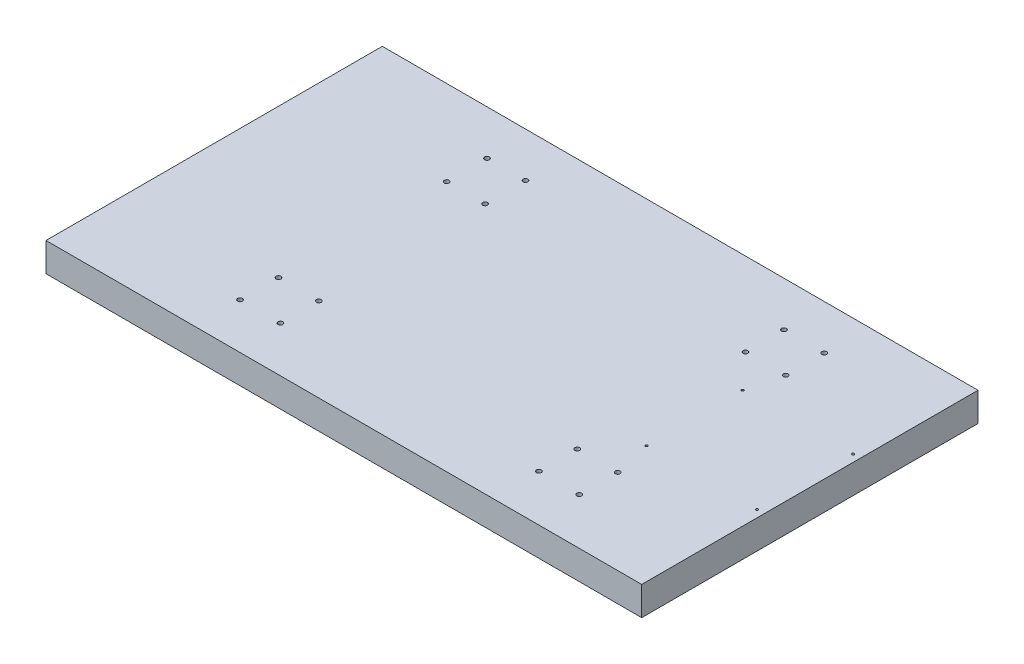
SolidWorks part; units mm, degrees
material "Plain Carbon Steel"
ref_plane "Front Plane" through (0, 0, 0) normal (0, 0, 1) x (1, 0, 0)
ref_plane "Top Plane" through (0, 0, 0) normal (0, 1, 0) x (1, 0, 0)
ref_plane "Right Plane" through (0, 0, 0) normal (1, 0, 0) x (0, 0, -1)
sketch "Sketch1" plane through (0, 0, 0) normal (0, 1, 0) x (1, 0, 0)
  line L0 (-418.465, 316.23) -> (418.465, 316.23) construction
  line L1 (418.465, 316.23) -> (418.465, -316.23) construction
  line L2 (418.465, -316.23) -> (-418.465, -316.23) construction
  line L3 (-418.465, -316.23) -> (-418.465, 316.23) construction
  line L4 (0, 316.23) -> (0, -316.23) construction
  line L6 (-876.3, 444.5) -> (876.3, 444.5)
  line L7 (-876.3, 444.5) -> (-876.3, -444.5)
  line L8 (-876.3, -444.5) -> (876.3, -444.5)
  line L9 (876.3, 444.5) -> (876.3, -444.5)
  line L10 (-876.3, 444.5) -> (876.3, -444.5) construction
  line L11 (-876.3, -444.5) -> (876.3, 444.5) construction
  point P10 (0, 0)
  point P11 (0, 0)
  dimension "D4" = 1752.6
  dimension "D5" = 889
extrude "Boss-Extrude1" add sketch "Sketch1" along normal blind 76.2
sketch "Sketch2" plane through (-876.3, 0, 0) normal (-1, 0, 0) x (0, 0, 1)
  line L4 (-444.5, 0) -> (444.5, 0)
  line L5 (444.5, 0) -> (444.5, 76.2)
  line L6 (444.5, 76.2) -> (-444.5, 76.2)
  line L7 (-444.5, 76.2) -> (-444.5, 0)
  line L8 (-444.5, 0) -> (444.5, 0)
  line L9 (444.5, 0) -> (444.5, 76.2)
  line L10 (444.5, 76.2) -> (-444.5, 76.2)
  line L11 (-444.5, 76.2) -> (-444.5, 0)
  dimension "D1" = 0
extrude "Boss-Extrude2" add sketch "Sketch2" along normal blind 330.2
sketch "Sketch4" plane through (876.3, 0, 0) normal (1, 0, 0) x (0, 0, -1)
  line L4 (-444.5, 0) -> (444.5, 0)
  line L5 (444.5, 0) -> (444.5, 76.2)
  line L6 (444.5, 76.2) -> (-444.5, 76.2)
  line L7 (-444.5, 76.2) -> (-444.5, 0)
  line L8 (-444.5, 0) -> (444.5, 0)
  line L9 (444.5, 0) -> (444.5, 76.2)
  line L10 (444.5, 76.2) -> (-444.5, 76.2)
  line L11 (-444.5, 76.2) -> (-444.5, 0)
  dimension "D1" = 0
extrude "Cut-Extrude1" cut sketch "Sketch4" against normal blind 508
sketch "Sketch5" plane through (0, 76.2, 0) normal (0, 1, 0) x (1, 0, 0)
  circle A0 centre (-811.5941, 219.722) radius 6.35
  circle A1 centre (-811.5941, 326.402) radius 6.35
  circle A2 centre (-709.9941, 326.402) radius 6.35
  circle A3 centre (-709.9941, 219.722) radius 6.35
  circle A4 centre (-26.7341, 326.402) radius 6.35
  circle A5 centre (79.9459, 326.402) radius 6.35
  circle A6 centre (79.9459, 224.802) radius 6.35
  circle A7 centre (-26.7341, 224.802) radius 6.35
  circle A8 centre (-26.7581, -219.722) radius 6.35
  circle A9 centre (79.9219, -219.722) radius 6.35
  circle A10 centre (79.9219, -321.322) radius 6.35
  circle A11 centre (-26.7581, -321.322) radius 6.35
  circle A12 centre (-707.4781, -222.262) radius 6.35
  circle A13 centre (-707.4781, -323.862) radius 6.35
  circle A14 centre (-814.1581, -323.862) radius 6.35
  circle A15 centre (-814.1581, -222.262) radius 6.35
  dimension "D1" = 12.7
extrude "Cut-Extrude2" cut sketch "Sketch5" against normal blind 73.66
sketch "Sketch7" plane through (0, 0, -444.5) normal (0, 0, -1) x (-1, 0, 0)
  circle A0 centre (190.5, 38.1) radius 6.35
  circle A1 centre (647.7, 38.1) radius 6.35
  dimension "D1" = 12.7
extrude "Cut-Extrude4" cut sketch "Sketch7" against normal blind 40.64
sketch "Sketch8" plane through (0, 76.2, 0) normal (0, 1, 0) x (1, 0, 0)
  circle A0 centre (349.25, 133.35) radius 3.175
  circle A1 centre (349.25, -120.65) radius 3.175
  circle A2 centre (57.15, -120.65) radius 3.175
  circle A3 centre (57.15, 133.35) radius 3.175
  dimension "D1" = 6.35
extrude "Cut-Extrude5" cut sketch "Sketch8" against normal blind 44.958
